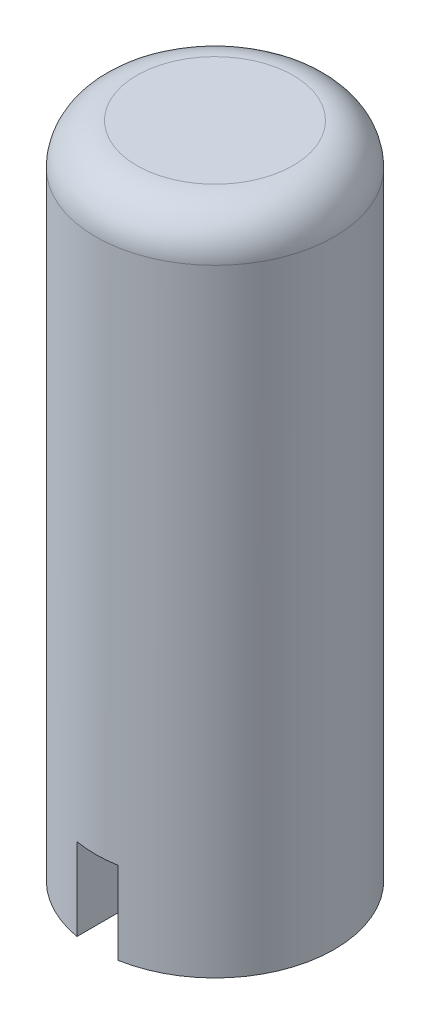
SolidWorks part; units mm, degrees
ref_plane "Front Plane" through (0, 0, 0) normal (0, 0, 1) x (1, 0, 0)
ref_plane "Top Plane" through (0, 0, 0) normal (0, 1, 0) x (1, 0, 0)
ref_plane "Right Plane" through (0, 0, 0) normal (1, 0, 0) x (0, 0, -1)
sketch "Sketch1" plane through (0, 0, 0) normal (0, 1, 0) x (1, 0, 0)
  circle A0 centre (0, 0) radius 2.9
  dimension "D1" = 5.8
extrude "Boss-Extrude1" add sketch "Sketch1" along normal blind 16
fillet "Fillet1" radius 1 1 edges at (0, 16, 2.9)
sketch "Sketch2" plane through (0, 0, 0) normal (0, -1, 0) x (1, 0, 0)
  line L1 (-2, -1.3) -> (0.6, -1.3)
  line L2 (-2, -1.3) -> (-2, 1.3)
  line L3 (-2, 1.3) -> (0.6, 1.3)
  line L4 (0.6, -1.3) -> (0.6, 1.3)
  line L5 (-2, -1.3) -> (0.6, 1.3) construction
  line L6 (-2, 1.3) -> (0.6, -1.3) construction
  point P0 (-0.7, 0)
  point P5 (0.5871, -0.2472)
  point P6 (-0.6721, -0.4558)
  dimension "D1" = 2.6
  dimension "D2" = 2.6
  dimension "D3" = 0.7
extrude "Cut-Extrude1" cut sketch "Sketch2" against normal blind 2.6
sketch "Sketch3" plane through (0, 0, 0) normal (0, -1, 0) x (1, 0, 0)
  line L1 (-0.5, -3.0574) -> (0.5, -3.0574)
  line L2 (-0.5, -3.0574) -> (-0.5, 3.0574)
  line L3 (-0.5, 3.0574) -> (0.5, 3.0574)
  line L4 (0.5, -3.0574) -> (0.5, 3.0574)
  line L5 (-0.5, -3.0574) -> (0.5, 3.0574) construction
  line L6 (-0.5, 3.0574) -> (0.5, -3.0574) construction
  point P0 (0, 0)
  dimension "D1" = 1
extrude "Cut-Extrude2" cut sketch "Sketch3" against normal blind 2
